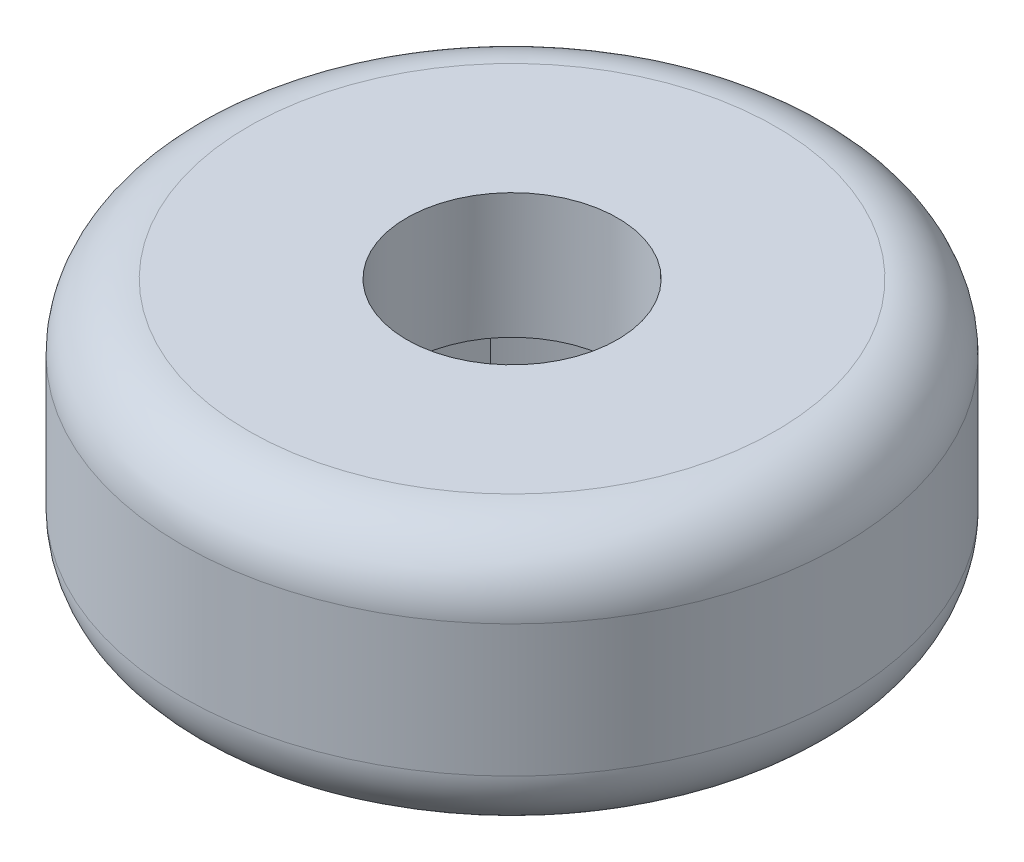
SolidWorks part; units mm, degrees
ref_plane "正面" through (0, 0, 0) normal (0, 0, 1) x (1, 0, 0)
ref_plane "平面" through (0, 0, 0) normal (0, 1, 0) x (1, 0, 0)
ref_plane "右側面" through (0, 0, 0) normal (1, 0, 0) x (0, 0, -1)
sketch "ｽｹｯﾁ1" plane through (0, 0, 0) normal (0, 1, 0) x (1, 0, 0)
  line L1 (-77.1853, 15.9281) -> (-72.9853, 15.9281)
  line L2 (-77.1853, 15.9281) -> (-77.1853, 11.3674)
  line L3 (-77.1853, 11.3674) -> (-72.9853, 11.3674)
  line L4 (-72.9853, 15.9281) -> (-72.9853, 11.3674)
  line L5 (-77.1853, 15.9281) -> (-72.9853, 11.3674) construction
  line L6 (-77.1853, 11.3674) -> (-72.9853, 15.9281) construction
  circle A0 centre (-75.0853, 13.6477) radius 3.1
  circle A1 centre (-75.0853, 13.6477) radius 5
  dimension "D1" = 6.2
  dimension "D3" = 10
  dimension "D2" = 4.2
extrude "ﾎﾞｽ - 押し出し1" add sketch "ｽｹｯﾁ1" along normal blind 4 contours A1 A0 | L4 A0 | L2 A0 | L1 A0 | L4 L1 L2 L3 | L3 A0
sketch "ｽｹｯﾁ2" plane through (0, 0, 0) normal (0, -1, 0) x (1, 0, 0)
  line L3 (-77.4353, -11.626) -> (-72.7353, -11.626)
  line L4 (-77.4353, -11.626) -> (-77.4353, -15.6695)
  line L5 (-77.4353, -15.6695) -> (-72.7353, -15.6695)
  line L6 (-72.7353, -11.626) -> (-72.7353, -15.6695)
  line L7 (-77.4353, -11.626) -> (-72.7353, -15.6695) construction
  line L8 (-77.4353, -15.6695) -> (-72.7353, -11.626) construction
  circle A0 centre (-75.0853, -13.6477) radius 3.1 construction
  circle A1 centre (-75.0853, -13.6477) radius 3.1
  dimension "D1" = 4.7
extrude "ｶｯﾄ - 押し出し1" cut sketch "ｽｹｯﾁ2" against normal blind 2.1 contours L6 L3 L4 L5 | L3 A1 | L5 A1
sketch "ｽｹｯﾁ3" plane through (0, 4, 0) normal (0, 1, 0) x (1, 0, 0)
  circle A0 centre (0, 0) radius 1.6
  circle A1 centre (-75.0853, 13.6477) radius 1.6
  circle A2 centre (-75.0853, 13.6477) radius 5
  circle A3 centre (-75.0853, 13.6477) radius 5
  dimension "D1" = 3.2
  dimension "D3" = 3.2
  dimension "D2" = 0
extrude "ｶｯﾄ - 押し出し2" cut sketch "ｽｹｯﾁ3" against normal blind 3 contours A1
fillet "ﾌｨﾚｯﾄ1" radius 1 2 edges at (-75.0853, 0, -8.6477) (-75.0853, 4, -8.6477)
